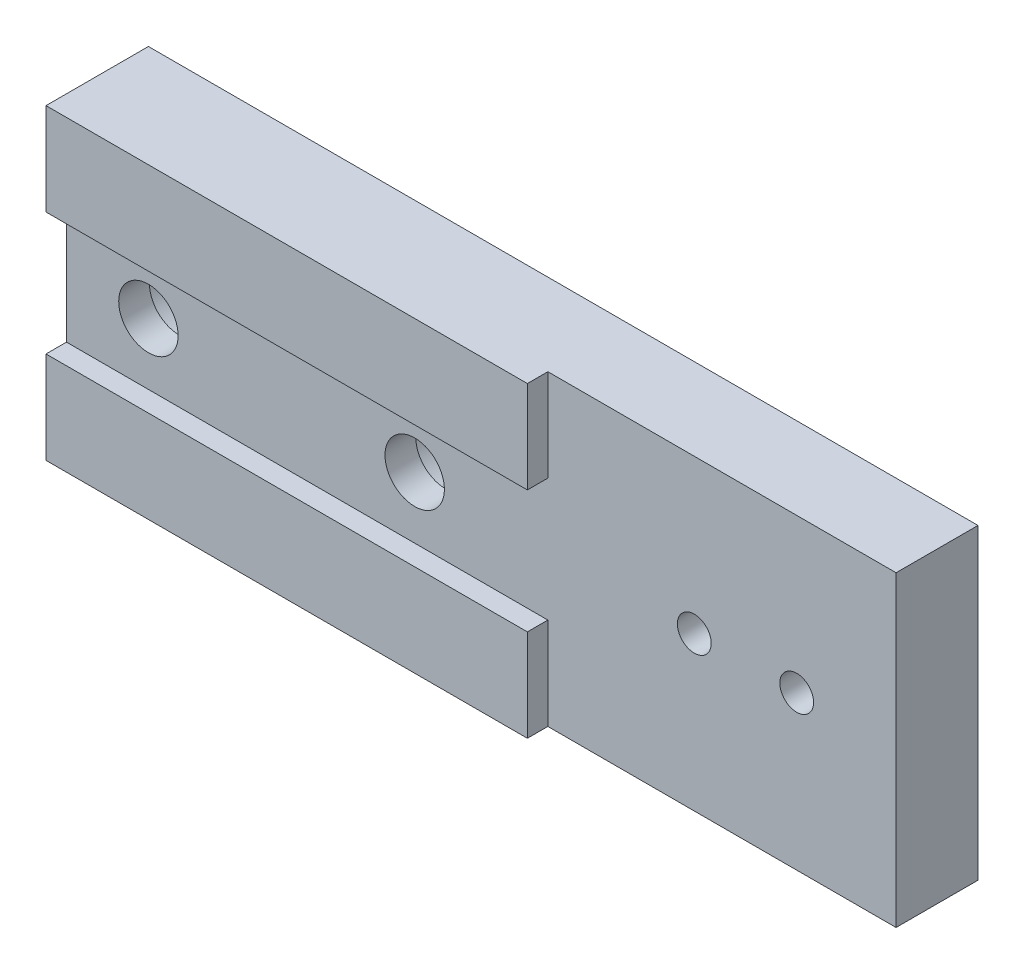
SolidWorks part; units mm, degrees
material "铝材"
ref_plane "前基準面" through (0, 0, 0) normal (0, 0, 1) x (1, 0, 0)
ref_plane "上基準面" through (0, 0, 0) normal (0, 1, 0) x (1, 0, 0)
ref_plane "右基準面" through (0, 0, 0) normal (1, 0, 0) x (0, 0, -1)
sketch "草图1" plane through (0, 0, 0) normal (0, 0, 1) x (1, 0, 0)
  line L1 (0, 0) -> (81, 0)
  line L2 (0, 0) -> (0, 30)
  line L3 (0, 30) -> (81, 30)
  line L4 (81, 0) -> (81, 30)
  dimension "D1" = 81
  dimension "D2" = 30
extrude "凸台-拉伸1" add sketch "草图1" along normal blind 10
hole_wizard "M5 六角凹头螺钉的柱形沉头孔1" positions "草图3" profile "草图2" counterbore size "M5" standard "ISO" end condition through all
sketch "草图3" plane through (0, 0, 0) normal (0, 0, -1) x (-1, 0, 0)
  line L1 (-81, 30) -> (0, 30) construction
  line L3 (0, 30) -> (0, 0) construction
  point P0 (-34, 15)
  point P1 (-8, 15)
  dimension "D1" = 26
  dimension "D2" = 15
  dimension "D3" = 8
sketch "草图2" plane through (34, 15, 0) normal (1, 0, 0) x (0, 1, 0)
  line L0 (0, 0) -> (0, 10)
  line L1 (0, 10) -> (2.9, 10)
  line L3 (2.9, 10) -> (2.9, 5)
  line L4 (2.9, 5) -> (5, 5)
  line L5 (5, 5) -> (5, 0)
  line L7 (5, 0) -> (0, 0)
  line L11 (0, -6.35) -> (0, 107.95) construction
  dimension "通孔孔直径" = 5.8
  dimension "通孔孔深度" = 10
  dimension "柱形沉头孔直径" = 10
  dimension "柱形沉头孔深度" = 5
sketch "草图4" plane through (0, 0, 10) normal (0, 0, 1) x (1, 0, 0)
  line L0 (0, 30) -> (0, 0) construction
  line L1 (0, 21) -> (81, 21)
  line L2 (0, 21) -> (0, 9)
  line L3 (0, 9) -> (81, 9)
  line L4 (81, 21) -> (81, 9)
  line L5 (81, 0) -> (81, 30) construction
  line L6 (34, 15) -> (8, 15) construction
  dimension "D1" = 12
extrude "切除-拉伸1" cut sketch "草图4" against normal blind 2
sketch "草图5" plane through (0, 21, 0) normal (0, -1, 0) x (1, 0, 0)
  line L0 (81, 8) -> (0, 8) construction
  line L1 (81, 10) -> (47, 10)
  line L2 (81, 10) -> (81, 8)
  line L3 (81, 8) -> (47, 8)
  line L4 (47, 10) -> (47, 8)
  dimension "D1" = 34
extrude "切除-拉伸2" cut sketch "草图5" against normal through all and the other way through all
hole_wizard "M4 螺纹孔1" positions "草图7" profile "草图6" tap size "M4" standard "ISO" end condition through all
sketch "草图7" plane through (0, 0, 8) normal (0, 0, 1) x (1, 0, 0)
  line L0 (81, 0) -> (81, 30) construction
  line L1 (47, 30) -> (81, 30) construction
  point P0 (71.3, 15)
  point P1 (61.3, 15)
  dimension "D1" = 10
  dimension "D2" = 9.7
  dimension "D3" = 15
sketch "草图6" plane through (71.3, 15, 8) normal (1, 0, 0) x (0, -1, 0)
  line L0 (0, 0) -> (0, 8)
  line L1 (0, 8) -> (1.65, 8)
  line L2 (1.65, 8) -> (1.65, 0)
  line L5 (1.65, 0) -> (0, 0)
  line L11 (0, -6.35) -> (0, 107.95) construction
  dimension "通孔螺纹孔钻头直径" = 3.3
  dimension "通孔螺纹孔钻头深度" = 8
cosmetic thread "孔螺蚊线1" parameters "D2"=4
cosmetic thread "孔螺蚊线2" parameters "D2"=4
